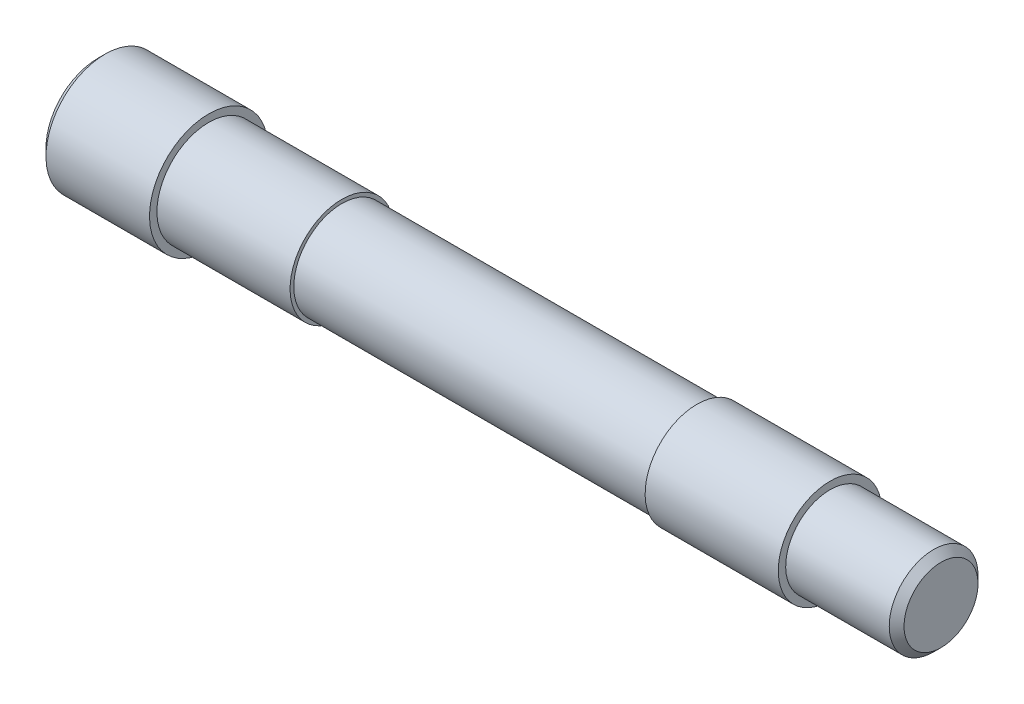
SolidWorks part; units mm, degrees
material "AISI 304"
ref_plane "Front Plane" through (0, 0, 0) normal (0, 0, 1) x (1, 0, 0)
ref_plane "Top Plane" through (0, 0, 0) normal (0, 1, 0) x (1, 0, 0)
ref_plane "Right Plane" through (0, 0, 0) normal (1, 0, 0) x (0, 0, -1)
sketch "Sketch2" plane through (0, 0, 0) normal (0, 0, 1) x (1, 0, 0)
  line L0 (0, 0) -> (0.0002, 0) construction
  line L1 (90.4875, 0) -> (-90.4875, 0) construction
  line L2 (-90.4875, 0) -> (-90.4875, 12.7)
  line L3 (-66.675, 0) -> (-66.675, 12.7)
  line L4 (-90.4875, 12.7) -> (-66.675, 12.7)
  line L5 (-38.1, 0) -> (-38.1, 11.1125)
  line L6 (-38.1, 11.1125) -> (-66.675, 11.1125)
  line L7 (0, -55) -> (0, 55) construction
  line L8 (38.1, 0) -> (38.1, 11.1125)
  line L9 (38.1, 11.1125) -> (66.675, 11.1125)
  line L10 (66.675, 11.1125) -> (66.675, 0)
  line L12 (0, 0) -> (0, 10.3187)
  line L13 (-38.1, 10.3187) -> (38.1, 10.3187)
  line L14 (-90.4875, 0) -> (66.675, 0)
  line L15 (66.675, 9.525) -> (90.4875, 9.525)
  line L16 (90.4875, 9.525) -> (90.4875, 0)
  line L17 (66.675, 0) -> (90.4875, 0)
  line L18 (-66.675, -22.225) -> (-52.3875, -22.225)
  line L20 (-66.675, -22.225) -> (-57.15, -22.225) construction
  point P5 (0, 0)
  point P25 (0, 10.3187)
  dimension "D1" = 12.7
  dimension "D2" = 23.8125
  dimension "D3" = 10.3187
  dimension "D4" = 11.1125
  dimension "D5" = 28.575
  dimension "D6" = 180.975
  dimension "D7" = 14.2875
  dimension "D8" = 9.525
revolve "Revolve1" add sketch "Sketch2" angle 360 about L1
chamfer "Chamfer4" distance 1.5875 angle 45 1 edges at (90.4875, 9.525, 0)
chamfer "Chamfer5" distance 1.5875 angle 45 1 edges at (-90.4875, 12.7, 0)
sketch "Sketch3" plane through (0, 0, 0) normal (0, 0, 1) x (1, 0, 0)
  line L0 (-66.675, -12.7) -> (-66.675, 12.7) construction
  line L1 (-66.675, -11.1125) -> (-38.1, -11.1125) construction
  line L2 (-52.3875, -1001.1389) -> (-52.3875, 48998.8611) construction
  line L3 (-52.3875, -11.1125) -> (-57.15, -11.1125)
  line L4 (-52.3875, -11.1125) -> (-52.3875, -6.35)
  line L5 (-52.3875, -6.35) -> (-57.15, -6.35)
  line L6 (-57.15, -6.35) -> (-57.15, -11.1125)
  dimension "D1" = 0
  dimension "D2" = 14.2875
revolve "Cut-Revolve1" cut sketch "Sketch3" angle 360 about L2
